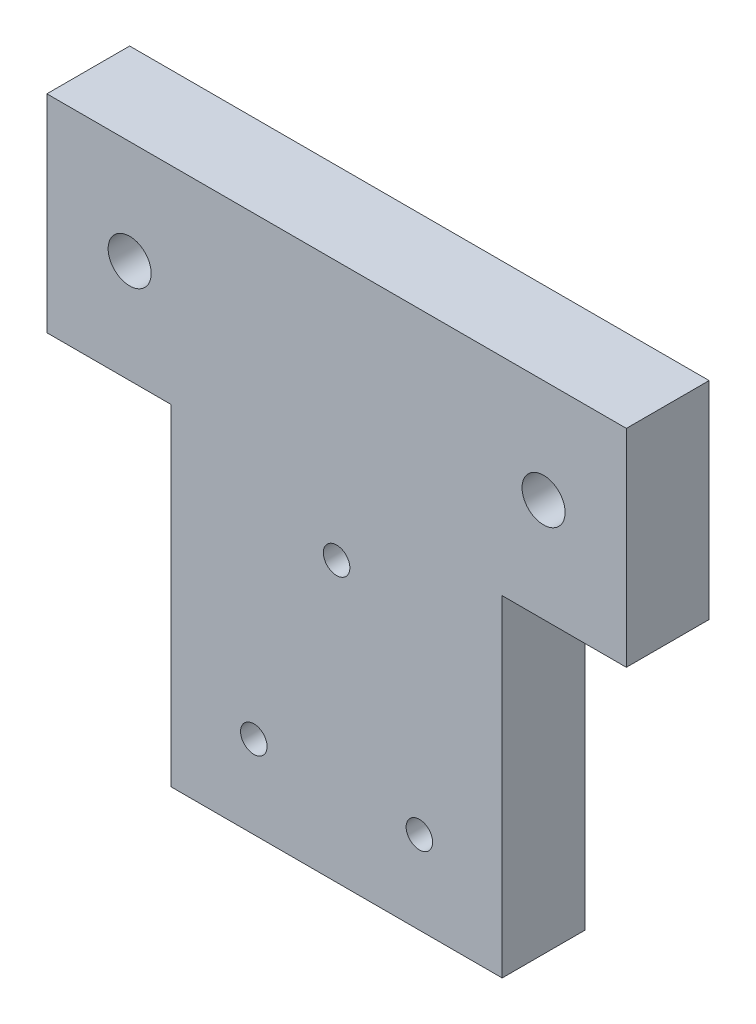
SolidWorks part; units mm, degrees
ref_plane "Front Plane" through (0, 0, 0) normal (0, 0, 1) x (1, 0, 0)
ref_plane "Top Plane" through (0, 0, 0) normal (0, 1, 0) x (1, 0, 0)
ref_plane "Right Plane" through (0, 0, 0) normal (1, 0, 0) x (0, 0, -1)
sketch "Sketch1" plane through (0, 0, 0) normal (0, 0, 1) x (1, 0, 0)
  line L0 (0, -65) -> (0, 19.867) construction
  line L1 (-35, 0) -> (35, 0)
  line L2 (35, 0) -> (35, -25)
  line L3 (35, -25) -> (20, -25)
  line L4 (20, -25) -> (20, -65)
  line L5 (20, -65) -> (-20, -65)
  line L6 (-20, -25) -> (-20, -65)
  line L7 (-35, -25) -> (-20, -25)
  line L8 (-35, 0) -> (-35, -25)
  point P13 (0, 0)
  dimension "D1" = 35
  dimension "D2" = 25
  dimension "D3" = 40
  dimension "D4" = 15
extrude "Boss-Extrude1" add sketch "Sketch1" along normal blind 10
sketch "Sketch6" plane through (0, 0, 0) normal (0, 0, -1) x (-1, 0, 0)
  line L0 (20, -25) -> (20, -65) construction
  line L1 (20, -65) -> (-20, -65) construction
  line L2 (0, -65) -> (0, 11.4537) construction
  circle A0 centre (10, -55) radius 1.6
  circle A1 centre (-10, -55) radius 1.6
  dimension "D1" = 3.2
  dimension "D4" = 3.2
  dimension "D2" = 10
  dimension "D3" = 10
extrude "Cut-Extrude1" cut sketch "Sketch6" against normal up to surface (10 mm away) up to face at (0, -28.75, 10)
sketch "Sketch7" plane through (0, 0, 0) normal (0, 0, -1) x (-1, 0, 0)
  line L0 (0, -65) -> (0, 0) construction
  line L1 (20, -65) -> (-20, -65) construction
  circle A0 centre (0, -31.3) radius 1.6
  circle A1 centre (10, -55) radius 1.6 construction
  dimension "D1" = 3.2
  dimension "D2" = 23.7
extrude "Cut-Extrude2" cut sketch "Sketch7" against normal up to surface (10 mm away) up to face at (-11.6, -55, 10)
sketch "Sketch9" plane through (0, 0, 10) normal (0, 0, 1) x (1, 0, 0)
  line L0 (-35, -12.5) -> (35, -12.5) construction
  line L1 (-35, 0) -> (-35, -25) construction
  line L2 (35, -25) -> (35, 0) construction
  line L3 (0, 0) -> (0, -65) construction
  line L4 (-20, -65) -> (20, -65) construction
  circle A0 centre (-25, -12.5) radius 2.6
  circle A1 centre (25, -12.5) radius 2.6
  point P15 (0, 0)
  dimension "D1" = 5.2
  dimension "D2" = 5.2
  dimension "D3" = 50
extrude "Cut-Extrude4" cut sketch "Sketch9" against normal up to surface (10 mm away) up to face at (-1.6, -31.3, 0)
